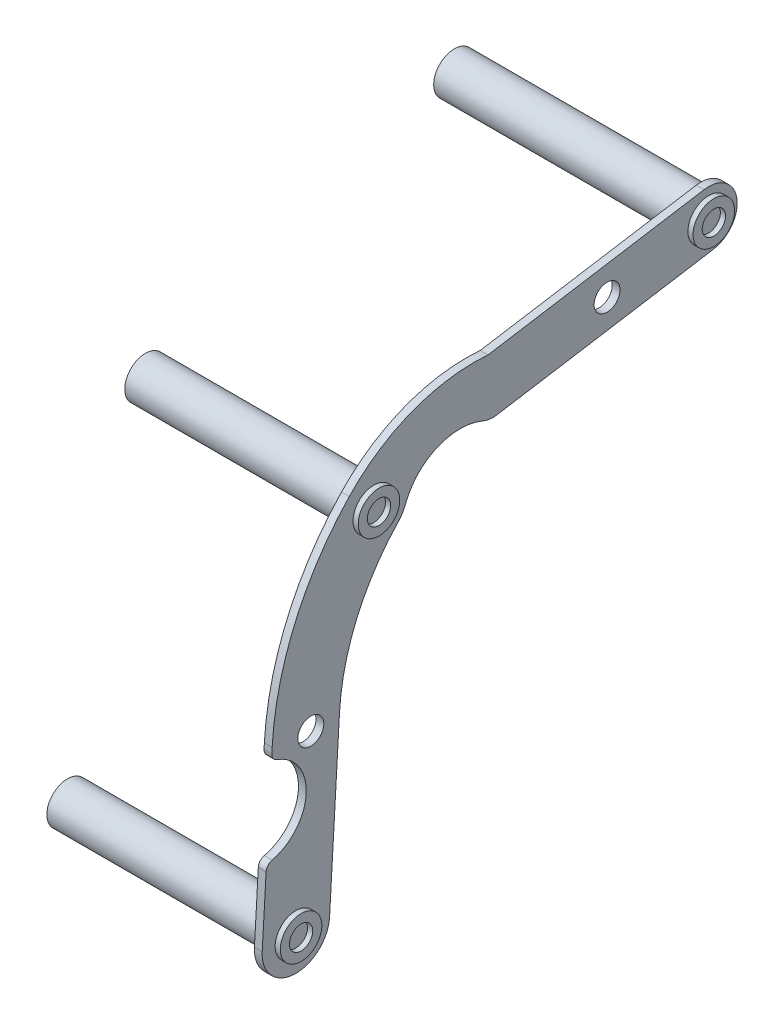
SolidWorks part; units mm, degrees
ref_plane "Front Plane" through (0, 0, 0) normal (0, 0, 1) x (1, 0, 0)
ref_plane "Top Plane" through (0, 0, 0) normal (0, 1, 0) x (1, 0, 0)
ref_plane "Right Plane" through (0, 0, 0) normal (1, 0, 0) x (0, 0, -1)
ref_plane "plate plane RH" through (40, 0, 0) normal (1, 0, 0) x (0, 0, -1)
ref_plane "plate plane LH" through (-40, 0, 0) normal (1, 0, 0) x (0, 0, -1)
sketch "Sketch1" plane through (0, 0, 0) normal (1, 0, 0) x (0, 0, -1)
  line L0 (0, 0) -> (0, 72.7594) construction
  line L1 (0, 0) -> (159.099, 159.099) construction
  circle A0 centre (0, 0) radius 8
  circle A1 centre (30.0312, 126.9975) radius 8
  circle A2 centre (159.099, 159.099) radius 8
  dimension "D1" = 16
  dimension "D2" = 130.5
  dimension "D3" = 133
  dimension "D4" = 225
  dimension "D5" = 45
extrude "mount tubes" add sketch "Sketch1" along normal mid plane 90
sketch "Sketch2" plane through (-45, 0, 0) normal (-1, 0, 0) x (0, 0, 1)
  circle A1 centre (-159.099, 159.099) radius 8
  circle A2 centre (-159.099, 159.099) radius 8
  dimension "D1" = 0
extrude "extend tube 1" add sketch "Sketch2" along normal blind 10
sketch "Sketch3" plane through (0, 0, 0) normal (1, 0, 0) x (0, 0, -1)
  circle A0 centre (0, 0) radius 4.5
  circle A1 centre (30.0312, 126.9975) radius 4.5
  circle A2 centre (159.099, 159.099) radius 4.5
  dimension "D1" = 9
extrude "mount tube holes" cut sketch "Sketch3" against normal through all and the other way through all
sketch "Sketch4" plane through (40, 0, 0) normal (1, 0, 0) x (0, 0, -1)
  line L0 (12.9784, -0.7493) -> (16.8076, 65.5721)
  line L1 (43.673, 134.2781) -> (71.5558, 138.8056) construction
  line L2 (77.6154, 134.724) -> (160.8621, 148.2412)
  line L3 (30.0312, 126.9975) -> (0, 0) construction
  line L4 (0, 0) -> (12.9784, -0.7493) construction
  line L5 (-12.9784, 0.7493) -> (-11.4807, 26.6891)
  line L6 (74.0893, 156.4396) -> (157.336, 169.9568)
  line L7 (-9.2683, 65.0078) -> (-9.1492, 67.0708)
  line L8 (-12.9784, 0.7493) -> (-9.1492, 67.0708) construction
  arc A0 (72.1084, 135.3884) -> (42.2228, 122.4848) centre (63.3237, 114.6742) ccw
  arc A1 (16.8076, 65.5721) -> (39.4754, 118.064) centre (100.0486, 60.766) cw
  arc A2 (72.1084, 135.3884) -> (77.6154, 134.724) centre (76.0127, 144.5948) ccw
  arc A3 (-9.1492, 67.0708) -> (20.5871, 135.9311) centre (100.0486, 60.766) cw
  arc A4 (12.9784, -0.7493) -> (-12.9784, 0.7493) centre (0, 0) cw
  arc A5 (42.2228, 122.4848) -> (39.4754, 118.064) centre (30.0312, 126.9975) cw
  arc A6 (20.5871, 135.9311) -> (74.0893, 156.4396) centre (68.7226, 90.3983) cw
  arc A7 (157.336, 169.9568) -> (160.8621, 148.2412) centre (159.099, 159.099) cw
  circle A8 centre (0, 0) radius 13 construction
  arc A9 (-9.1628, 29.4387) -> (-7.2823, 62.0096) centre (-13, 46) ccw
  circle A10 centre (-13, 46) radius 17 construction
  circle A11 centre (30.0312, 126.9975) radius 13 construction
  circle A12 centre (0, 0) radius 8 construction
  circle A13 centre (159.099, 159.099) radius 8 construction
  circle A14 centre (159.099, 159.099) radius 11 construction
  circle A15 centre (30.0312, 126.9975) radius 8 construction
  circle A16 centre (-13, 46) radius 16 construction
  arc A17 (-9.1628, 29.4387) -> (-11.4807, 26.6891) centre (-8.4857, 26.5161) ccw
  arc A18 (-9.2683, 65.0078) -> (-7.2823, 62.0096) centre (-6.2733, 64.8349) ccw
  point P45 (-9.4064, 62.6158)
  dimension "D1" = 26
  dimension "D2" = 26
  dimension "D3" = 22
  dimension "D5" = 32
  dimension "D7" = 45
  dimension "D10" = 10
  dimension "D14" = 3
  dimension "D15" = 3
  dimension "D4" = 46
  dimension "D6" = 13
  dimension "D8" = 5
  dimension "D9" = 10
  dimension "D11" = 26
  dimension "D12" = 22
  dimension "D13" = 1
extrude "Side plate RH" add sketch "Sketch4" along normal blind 3
sketch "motor mount holes" plane through (0, 0, 0) normal (1, 0, 0) x (0, 0, -1)
  line L0 (76.7336, 145.7249) -> (139.4853, 155.9142) construction
  line L1 (77.6154, 134.724) -> (160.8621, 148.2412) construction
  line L2 (2.8862, 15.2909) -> (5.7792, 65.3978) construction
  line L3 (12.9784, -0.7493) -> (16.8076, 65.5721) construction
  circle A0 centre (119.9387, 152.7403) radius 5
  circle A1 centre (5.7562, 65) radius 5
  dimension "D2" = 10
  dimension "D1" = 144
  dimension "D3" = 11
  dimension "D4" = 11
  dimension "D5" = 65
extrude "motor mount holes f" cut sketch "motor mount holes" along normal through all
